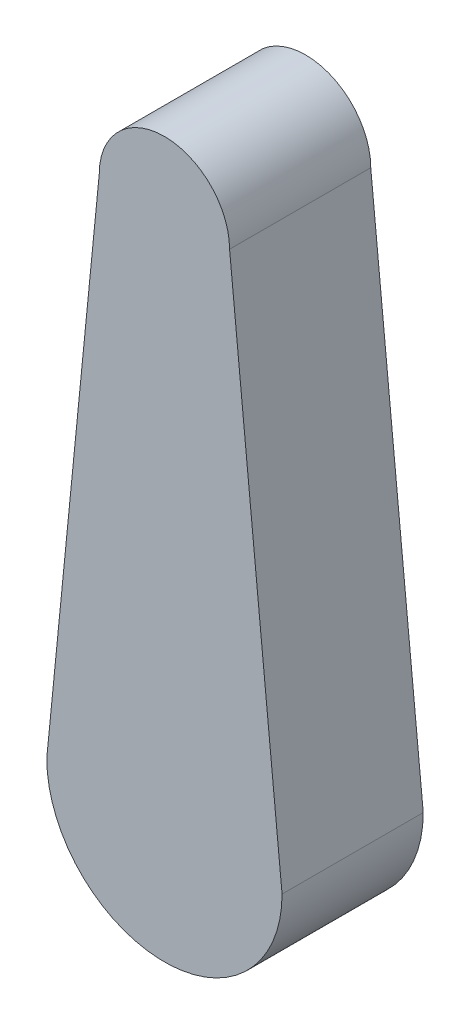
SolidWorks part; units mm, degrees
ref_plane "Płaszczyzna przednia" through (0, 0, 0) normal (0, 0, 1) x (1, 0, 0)
ref_plane "Płaszczyzna górna" through (0, 0, 0) normal (0, 1, 0) x (1, 0, 0)
ref_plane "Płaszczyzna prawa" through (0, 0, 0) normal (1, 0, 0) x (0, 0, -1)
sketch "Szkic1" plane through (0, 0, 0) normal (0, 0, 1) x (1, 0, 0)
  line L2 (-194.0811, 106.3248) -> (-196.9811, 76.9248)
  line L3 (-183.9811, 76.9248) -> (-186.8811, 106.3248)
  arc A2 (-196.9811, 76.9248) -> (-183.9811, 76.9248) centre (-190.4811, 76.9248) ccw
  arc A3 (-186.8811, 106.3248) -> (-194.0811, 106.3248) centre (-190.4811, 106.3248) ccw
  dimension "D1" = 6.5
  dimension "D2" = 3.6
  dimension "D3" = 0
  dimension "D4" = 29.4
extrude "Dodanie-wyciągnięcie1" add sketch "Szkic1" against normal blind 7.8
